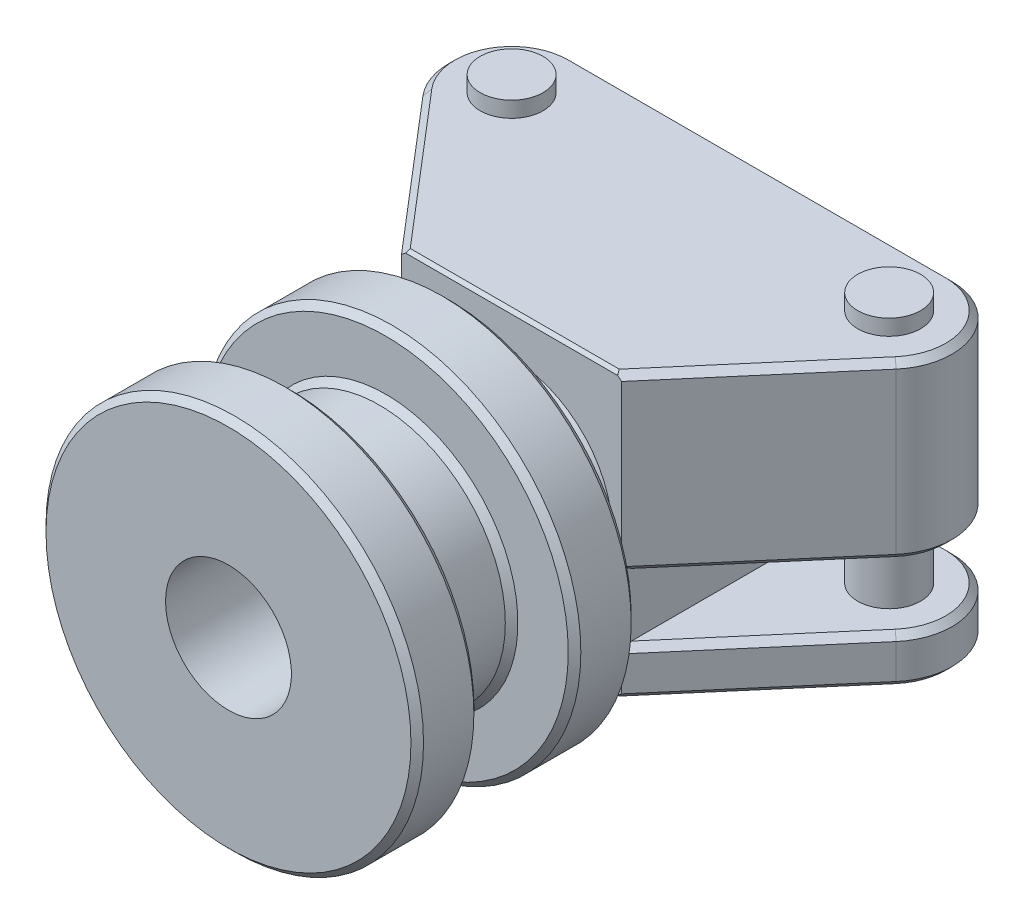
SolidWorks part; units mm, degrees
ref_plane "Front Plane" through (0, 0, 0) normal (0, 0, 1) x (1, 0, 0)
ref_plane "Top Plane" through (0, 0, 0) normal (0, 1, 0) x (1, 0, 0)
ref_plane "Right Plane" through (0, 0, 0) normal (1, 0, 0) x (0, 0, -1)
sketch "Sketch1" plane through (0, 0, 0) normal (0, 0, 1) x (1, 0, 0)
  circle A0 centre (0, 0) radius 6
  dimension "D1" = 12
extrude "Boss-Extrude1" add sketch "Sketch1" along normal blind 2
sketch "Sketch2" plane through (0, 0, 0) normal (0, 0, -1) x (-1, 0, 0)
  circle A0 centre (0, 0) radius 4
  dimension "D1" = 8
extrude "Boss-Extrude2" add sketch "Sketch2" along normal blind 3
sketch "Sketch3" plane through (0, 0, -3) normal (0, 0, -1) x (-1, 0, 0)
  circle A0 centre (0, 0) radius 6 construction
  circle A1 centre (0, 0) radius 6
extrude "Boss-Extrude3" add sketch "Sketch3" along normal blind 2
sketch "Sketch4" plane through (0, 0, -5) normal (0, 0, -1) x (-1, 0, 0)
  circle A0 centre (0, 0) radius 3
  dimension "D1" = 6
extrude "Boss-Extrude4" add sketch "Sketch4" along normal blind 2
sketch "Sketch5" plane through (0, 0, 0) normal (0, 1, 0) x (1, 0, 0)
  line L0 (0, -2) -> (0, 15) construction
  line L1 (-6, -2) -> (6, -2) construction
  line L2 (3.5, 7) -> (-3.5, 7)
  line L3 (3, 7) -> (-3, 7) construction
  line L4 (-3.5, 7) -> (-7.5199, 11.7)
  line L5 (-6, 15) -> (6, 15)
  line L6 (0, 15) -> (0, 7) construction
  line L7 (-8, 13) -> (-8, -2) construction
  line L8 (3.5, 7) -> (7.5199, 11.7)
  arc A0 (-7.5199, 11.7) -> (-6, 15) centre (-6, 13) cw
  circle A1 centre (-6, 13) radius 1
  circle A2 centre (6, 13) radius 1
  arc A3 (7.5199, 11.7) -> (6, 15) centre (6, 13) ccw
  dimension "D3" = 2
  dimension "D4" = 2
  dimension "D6" = 4.5
  dimension "D1" = 17
  dimension "D2" = 8
  dimension "D5" = 6
extrude "Boss-Extrude5" add sketch "Sketch5" along normal mid plane 9
sketch "Sketch6" plane through (0, 0, -15) normal (0, 0, -1) x (-1, 0, 0)
  line L0 (-8, 4.5) -> (-8, -4.5) construction
  line L1 (-8, -1) -> (-3.5, -1)
  line L2 (-8, -1) -> (-8, -3)
  line L3 (-8, -3) -> (-3.5, -3)
  line L4 (-3.5, -1) -> (-3.5, -3)
  line L10 (-6, -4.5) -> (6, -4.5) construction
  line L12 (0, 4.5394) -> (0, -4.5394) construction
  line L13 (0, 0) -> (-8, 0) construction
  line L18 (8, 1) -> (3.5, 1)
  line L19 (8, 1) -> (8, 3)
  line L20 (8, 3) -> (3.5, 3)
  line L21 (3.5, 1) -> (3.5, 3)
  dimension "D1" = 1.5
  dimension "D2" = 2
  dimension "D4" = 4.5
extrude "Cut-Extrude1" cut sketch "Sketch6" against normal up to surface (8 mm away) up to face at (-3, 0, -7)
sketch "Sketch7" plane through (0, 0, -15) normal (0, 0, -1) x (-1, 0, 0)
  circle A0 centre (0, 0) radius 2
  dimension "D1" = 4
extrude "Cut-Extrude2" cut sketch "Sketch7" against normal through all
chamfer "Chamfer1" distance 0.2 angle 45 32 edges at (6, 0, 2) (-4, 0, -3) (6, 0, 0) (-4, 0, 0) (-6, 0, -3) (-6, 0, -5) (-3, 0, -5) (-3, 0, -7) (-5.51, 3, -9.35) (-5.51, 1, -9.35) (-7.8166, 3, -13.8367) (-7.8166, 1, -13.8367) (-4.75, 3, -15) (-4.75, 1, -15) (-3.5, 2, -15) (3.5, -2, -15) (4.75, -3, -15) (5.51, -3, -9.35) (7.8166, -3, -13.8367) (5.51, -1, -9.35) (4.75, -1, -15) (7.8166, -1, -13.8367) (5.51, -4.5, -9.35) (-5.51, -4.5, -9.35) (7.8166, -4.5, -13.8367) (-7.8166, -4.5, -13.8367) (0, -4.5, -15) (5.51, 4.5, -9.35) (-5.51, 4.5, -9.35) (7.8166, 4.5, -13.8367) (-7.8166, 4.5, -13.8367) (0, 4.5, -15)
chamfer "Chamfer2" distance 0.1 angle 45 4 edges at (-3.5, 2, -7) (3.5, -2, -7) (0, -4.5, -7) (0, 4.5, -7)
sketch "Sketch8" plane through (0, 4.5, 0) normal (0, 1, 0) x (1, 0, 0)
  circle A0 centre (-6, 13) radius 1 construction
  circle A1 centre (-6, 13) radius 1
extrude "Boss-Extrude6" add sketch "Sketch8" along normal blind 0.5 and the other way blind 9.5 separate body
sketch "Sketch9" plane through (0, 4.5, 0) normal (0, 1, 0) x (1, 0, 0)
  circle A0 centre (6, 13) radius 1 construction
  circle A1 centre (6, 13) radius 1
extrude "Boss-Extrude7" add sketch "Sketch9" along normal blind 0.5 and the other way blind 9.5 separate body
